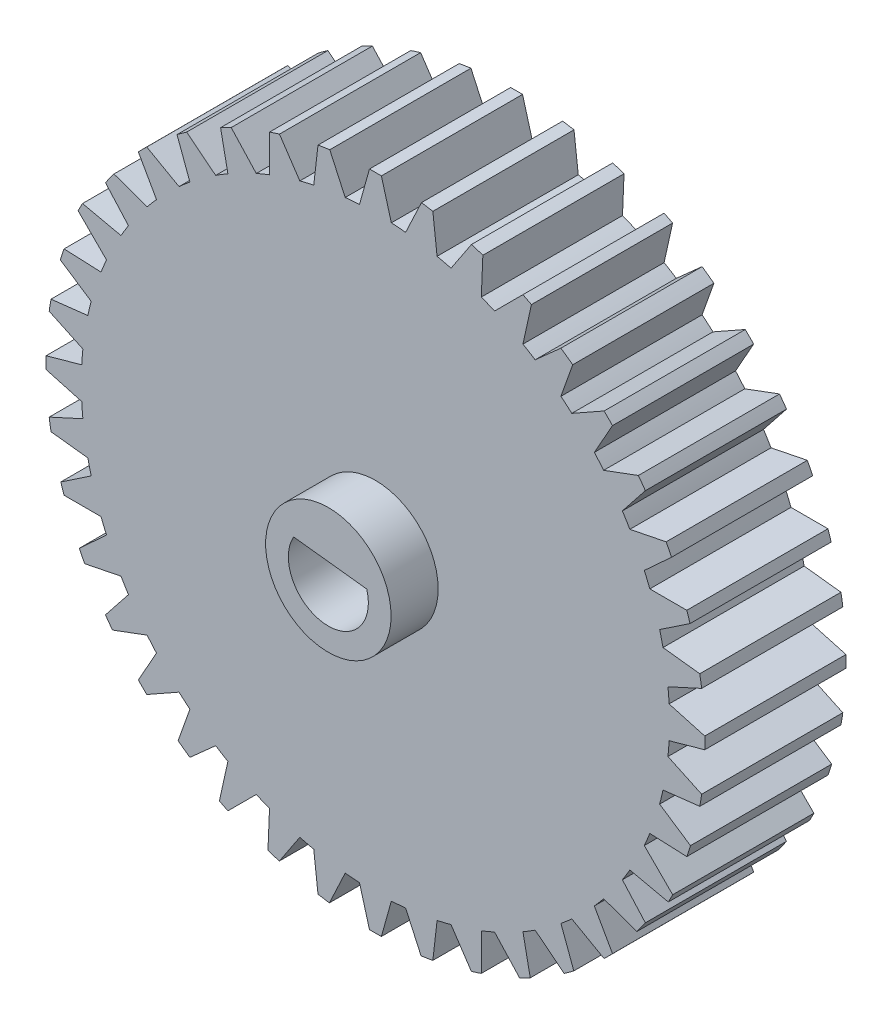
SolidWorks part; units mm, degrees
ref_plane "前视基准面" through (0, 0, 0) normal (0, 0, 1) x (1, 0, 0)
ref_plane "上视基准面" through (0, 0, 0) normal (0, 1, 0) x (1, 0, 0)
ref_plane "右视基准面" through (0, 0, 0) normal (1, 0, 0) x (0, 0, -1)
other "Configuration Table"
sketch "草图1" plane through (0, 0, 0) normal (0, 0, 1) x (1, 0, 0)
  line L0 (4.894, 1.4347) -> (-4.4239, 2.5376)
  circle A0 centre (0, 0) radius 8
  arc A1 (-4.4239, 2.5376) -> (4.894, 1.4347) centre (0, 0) ccw
extrude "凸台-拉伸1" add sketch "草图1" along normal blind 24
sketch "草图2" plane through (0, 0, 0) normal (0, 0, 1) x (1, 0, 0)
  circle A0 centre (0, 0) radius 37.5
  circle A1 centre (0, 0) radius 8
extrude "凸台-拉伸2" add sketch "草图2" along normal blind 18
sketch "草图3" plane through (0, 0, 0) normal (0, 0, 1) x (1, 0, 0)
  line L0 (37.445, 2.0305) -> (41.9931, 0.7606)
  line L1 (41.9931, -0.7606) -> (37.445, -2.0305)
  arc A0 (37.445, -2.0305) -> (37.445, 2.0305) centre (0, 0) ccw
  arc A1 (41.9931, 0.7606) -> (41.9931, -0.7606) centre (0, 0) cw
extrude "凸台-拉伸3" add sketch "草图3" along normal blind 18
sketch "草图4" plane through (0, 0, 0) normal (0, 0, 1) x (1, 0, 0)
  line L0 (36.6663, 7.8632) -> (41.3571, 7.3204)
  line L1 (41.5951, 5.8179) -> (37.3016, 3.8521)
  arc A0 (37.3016, 3.8521) -> (36.6663, 7.8632) centre (0, 0) ccw
  arc A1 (41.3571, 7.3204) -> (41.5951, 5.8179) centre (0, 0) cw
extrude "凸台-拉伸4" add sketch "草图4" along normal blind 18
sketch "草图5" plane through (0, 0, 0) normal (0, 0, 1) x (1, 0, 0)
  line L0 (34.9848, 13.5023) -> (39.7028, 13.5023)
  line L1 (40.1116, 12.2345) -> (36.2398, 9.64)
  arc A0 (36.2398, 9.64) -> (34.9848, 13.5023) centre (0, 0) ccw
  arc A1 (39.7028, 13.5023) -> (40.1116, 12.2345) centre (0, 0) cw
extrude "凸台-拉伸5" add sketch "草图5" along normal blind 18
sketch "草图6" plane through (0, 0, 0) normal (0, 0, 1) x (1, 0, 0)
  line L0 (32.4419, 18.8089) -> (37.0708, 19.7422)
  line L1 (37.7615, 18.3868) -> (34.2856, 15.1904)
  arc A0 (34.2856, 15.1904) -> (32.4419, 18.8089) centre (0, 0) ccw
  arc A1 (37.0708, 19.7422) -> (37.7615, 18.3868) centre (0, 0) cw
extrude "凸台-拉伸6" add sketch "草图6" along normal blind 18
sketch "草图7" plane through (0, 0, 0) normal (0, 0, 1) x (1, 0, 0)
  line L0 (29.1001, 23.6524) -> (33.5261, 25.2983)
  line L1 (34.4202, 24.0676) -> (31.4872, 20.3669)
  arc A0 (31.4872, 20.3669) -> (29.1001, 23.6524) centre (0, 0) ccw
  arc A1 (33.5261, 25.2983) -> (34.4202, 24.0676) centre (0, 0) cw
extrude "凸台-拉伸7" add sketch "草图7" along normal blind 18
sketch "草图8" plane through (0, 0, 0) normal (0, 0, 1) x (1, 0, 0)
  line L0 (25.0418, 27.9134) -> (29.1558, 30.2315)
  line L1 (30.2315, 29.1558) -> (27.9134, 25.0418)
  arc A0 (27.9134, 25.0418) -> (25.0418, 27.9134) centre (0, 0) ccw
  arc A1 (29.1558, 30.2315) -> (30.2315, 29.1558) centre (0, 0) cw
extrude "凸台-拉伸8" add sketch "草图8" along normal blind 18
sketch "草图9" plane through (0, 0, 0) normal (0, 0, 1) x (1, 0, 0)
  line L0 (20.3669, 31.4872) -> (23.6524, 34.4202)
  line L1 (25.1558, 33.3372) -> (23.6524, 29.1001)
  arc A0 (23.6524, 29.1001) -> (20.3669, 31.4872) centre (0, 0) ccw
  arc A1 (23.6524, 34.4202) -> (25.1558, 33.3372) centre (0, 0) cw
extrude "凸台-拉伸9" add sketch "草图9" along normal blind 18
sketch "草图10" plane through (0, 0, 0) normal (0, 0, 1) x (1, 0, 0)
  line L0 (15.1904, 34.2856) -> (18.8089, 37.904)
  line L1 (19.8899, 37.3481) -> (18.8089, 32.4419)
  arc A0 (18.8089, 32.4419) -> (15.1904, 34.2856) centre (0, 0) ccw
  arc A1 (18.8089, 37.904) -> (19.8899, 37.3481) centre (0, 0) cw
extrude "凸台-拉伸10" add sketch "草图10" along normal blind 18
sketch "草图11" plane through (0, 0, 0) normal (0, 0, 1) x (1, 0, 0)
  line L0 (9.64, 36.2398) -> (12.2532, 40.1729)
  line L1 (13.7, 39.7028) -> (13.5023, 34.9848)
  arc A0 (13.5023, 34.9848) -> (9.64, 36.2398) centre (0, 0) ccw
  arc A1 (12.2532, 40.1729) -> (13.7, 39.7028) centre (0, 0) cw
extrude "凸台-拉伸11" add sketch "草图11" along normal blind 18
sketch "草图12" plane through (0, 0, 0) normal (0, 0, 1) x (1, 0, 0)
  line L0 (3.8521, 37.3016) -> (5.8663, 41.5951)
  line L1 (7.3216, 41.3637) -> (7.8632, 36.6663)
  arc A0 (7.8632, 36.6663) -> (3.8521, 37.3016) centre (0, 0) ccw
  arc A1 (5.8663, 41.5951) -> (7.3216, 41.3637) centre (0, 0) cw
extrude "凸台-拉伸12" add sketch "草图12" along normal blind 18
sketch "草图13" plane through (0, 0, 0) normal (0, 0, 1) x (1, 0, 0)
  line L0 (-2.0305, 37.445) -> (-0.7606, 41.9931)
  line L1 (0.7606, 41.9931) -> (2.0305, 37.445)
  arc A0 (2.0305, 37.445) -> (-2.0305, 37.445) centre (0, 0) ccw
  arc A1 (-0.7606, 41.9931) -> (0.7606, 41.9931) centre (0, 0) cw
extrude "凸台-拉伸13" add sketch "草图13" along normal blind 18
sketch "草图14" plane through (0, 0, 0) normal (0, 0, 1) x (1, 0, 0)
  line L0 (-7.8632, 36.6663) -> (-7.3204, 41.3571)
  line L1 (-5.8179, 41.5951) -> (-3.8521, 37.3016)
  arc A0 (-3.8521, 37.3016) -> (-7.8632, 36.6663) centre (0, 0) ccw
  arc A1 (-7.3204, 41.3571) -> (-5.8179, 41.5951) centre (0, 0) cw
extrude "凸台-拉伸14" add sketch "草图14" along normal blind 18
sketch "草图15" plane through (0, 0, 0) normal (0, 0, 1) x (1, 0, 0)
  line L0 (-13.5023, 34.9848) -> (-13.5023, 39.7028)
  line L1 (-12.2345, 40.1116) -> (-9.64, 36.2398)
  arc A0 (-9.64, 36.2398) -> (-13.5023, 34.9848) centre (0, 0) ccw
  arc A1 (-13.5023, 39.7028) -> (-12.2345, 40.1116) centre (0, 0) cw
extrude "凸台-拉伸15" add sketch "草图15" along normal blind 18
sketch "草图16" plane through (0, 0, 0) normal (0, 0, 1) x (1, 0, 0)
  line L0 (-18.8089, 32.4419) -> (-19.7422, 37.0708)
  line L1 (-18.3868, 37.7615) -> (-15.1904, 34.2856)
  arc A0 (-15.1904, 34.2856) -> (-18.8089, 32.4419) centre (0, 0) ccw
  arc A1 (-19.7422, 37.0708) -> (-18.3868, 37.7615) centre (0, 0) cw
extrude "凸台-拉伸16" add sketch "草图16" along normal blind 18
sketch "草图17" plane through (0, 0, 0) normal (0, 0, 1) x (1, 0, 0)
  line L0 (-23.6524, 29.1001) -> (-25.2983, 33.5261)
  line L1 (-24.0676, 34.4202) -> (-20.3669, 31.4872)
  arc A0 (-20.3669, 31.4872) -> (-23.6524, 29.1001) centre (0, 0) ccw
  arc A1 (-25.2983, 33.5261) -> (-24.0676, 34.4202) centre (0, 0) cw
extrude "凸台-拉伸17" add sketch "草图17" along normal blind 18
sketch "草图18" plane through (0, 0, 0) normal (0, 0, 1) x (1, 0, 0)
  line L0 (-27.9134, 25.0418) -> (-30.2315, 29.1558)
  line L1 (-29.1558, 30.2315) -> (-25.0418, 27.9134)
  arc A0 (-25.0418, 27.9134) -> (-27.9134, 25.0418) centre (0, 0) ccw
  arc A1 (-30.2315, 29.1558) -> (-29.1558, 30.2315) centre (0, 0) cw
extrude "凸台-拉伸18" add sketch "草图18" along normal blind 18
sketch "草图19" plane through (0, 0, 0) normal (0, 0, 1) x (1, 0, 0)
  line L0 (-31.4872, 20.3669) -> (-34.4202, 23.6524)
  line L1 (-33.3372, 25.1558) -> (-29.1001, 23.6524)
  arc A0 (-29.1001, 23.6524) -> (-31.4872, 20.3669) centre (0, 0) ccw
  arc A1 (-34.4202, 23.6524) -> (-33.3372, 25.1558) centre (0, 0) cw
extrude "凸台-拉伸19" add sketch "草图19" along normal blind 18
sketch "草图20" plane through (0, 0, 0) normal (0, 0, 1) x (1, 0, 0)
  line L0 (-34.2856, 15.1904) -> (-37.904, 18.8089)
  line L1 (-37.3481, 19.8899) -> (-32.4419, 18.8089)
  arc A0 (-32.4419, 18.8089) -> (-34.2856, 15.1904) centre (0, 0) ccw
  arc A1 (-37.904, 18.8089) -> (-37.3481, 19.8899) centre (0, 0) cw
extrude "凸台-拉伸20" add sketch "草图20" along normal blind 18
sketch "草图21" plane through (0, 0, 0) normal (0, 0, 1) x (1, 0, 0)
  line L0 (-36.2398, 9.64) -> (-40.1729, 12.2532)
  line L1 (-39.7028, 13.7) -> (-34.9848, 13.5023)
  arc A0 (-34.9848, 13.5023) -> (-36.2398, 9.64) centre (0, 0) ccw
  arc A1 (-40.1729, 12.2532) -> (-39.7028, 13.7) centre (0, 0) cw
extrude "凸台-拉伸21" add sketch "草图21" along normal blind 18
sketch "草图22" plane through (0, 0, 0) normal (0, 0, 1) x (1, 0, 0)
  line L0 (-37.3016, 3.8521) -> (-41.5951, 5.8663)
  line L1 (-41.3637, 7.3216) -> (-36.6663, 7.8632)
  arc A0 (-36.6663, 7.8632) -> (-37.3016, 3.8521) centre (0, 0) ccw
  arc A1 (-41.5951, 5.8663) -> (-41.3637, 7.3216) centre (0, 0) cw
extrude "凸台-拉伸22" add sketch "草图22" along normal blind 18
sketch "草图23" plane through (0, 0, 0) normal (0, 0, 1) x (1, 0, 0)
  line L0 (-37.445, -2.0305) -> (-41.9931, -0.7606)
  line L1 (-41.9931, 0.7606) -> (-37.445, 2.0305)
  arc A0 (-37.445, 2.0305) -> (-37.445, -2.0305) centre (0, 0) ccw
  arc A1 (-41.9931, -0.7606) -> (-41.9931, 0.7606) centre (0, 0) cw
extrude "凸台-拉伸23" add sketch "草图23" along normal blind 18
sketch "草图24" plane through (0, 0, 0) normal (0, 0, 1) x (1, 0, 0)
  line L0 (-36.6663, -7.8632) -> (-41.3571, -7.3204)
  line L1 (-41.5951, -5.8179) -> (-37.3016, -3.8521)
  arc A0 (-37.3016, -3.8521) -> (-36.6663, -7.8632) centre (0, 0) ccw
  arc A1 (-41.3571, -7.3204) -> (-41.5951, -5.8179) centre (0, 0) cw
extrude "凸台-拉伸24" add sketch "草图24" along normal blind 18
sketch "草图25" plane through (0, 0, 0) normal (0, 0, 1) x (1, 0, 0)
  line L0 (-34.9848, -13.5023) -> (-39.7028, -13.5023)
  line L1 (-40.1116, -12.2345) -> (-36.2398, -9.64)
  arc A0 (-36.2398, -9.64) -> (-34.9848, -13.5023) centre (0, 0) ccw
  arc A1 (-39.7028, -13.5023) -> (-40.1116, -12.2345) centre (0, 0) cw
extrude "凸台-拉伸25" add sketch "草图25" along normal blind 18
sketch "草图26" plane through (0, 0, 0) normal (0, 0, 1) x (1, 0, 0)
  line L0 (-32.4419, -18.8089) -> (-37.0708, -19.7422)
  line L1 (-37.7615, -18.3868) -> (-34.2856, -15.1904)
  arc A0 (-34.2856, -15.1904) -> (-32.4419, -18.8089) centre (0, 0) ccw
  arc A1 (-37.0708, -19.7422) -> (-37.7615, -18.3868) centre (0, 0) cw
extrude "凸台-拉伸26" add sketch "草图26" along normal blind 18
sketch "草图27" plane through (0, 0, 0) normal (0, 0, 1) x (1, 0, 0)
  line L0 (-29.1001, -23.6524) -> (-33.5261, -25.2983)
  line L1 (-34.4202, -24.0676) -> (-31.4872, -20.3669)
  arc A0 (-31.4872, -20.3669) -> (-29.1001, -23.6524) centre (0, 0) ccw
  arc A1 (-33.5261, -25.2983) -> (-34.4202, -24.0676) centre (0, 0) cw
extrude "凸台-拉伸27" add sketch "草图27" along normal blind 18
sketch "草图28" plane through (0, 0, 0) normal (0, 0, 1) x (1, 0, 0)
  line L0 (-25.0418, -27.9134) -> (-29.1558, -30.2315)
  line L1 (-30.2315, -29.1558) -> (-27.9134, -25.0418)
  arc A0 (-27.9134, -25.0418) -> (-25.0418, -27.9134) centre (0, 0) ccw
  arc A1 (-29.1558, -30.2315) -> (-30.2315, -29.1558) centre (0, 0) cw
extrude "凸台-拉伸28" add sketch "草图28" along normal blind 18
sketch "草图29" plane through (0, 0, 0) normal (0, 0, 1) x (1, 0, 0)
  line L0 (-20.3669, -31.4872) -> (-23.6524, -34.4202)
  line L1 (-25.1558, -33.3372) -> (-23.6524, -29.1001)
  arc A0 (-23.6524, -29.1001) -> (-20.3669, -31.4872) centre (0, 0) ccw
  arc A1 (-23.6524, -34.4202) -> (-25.1558, -33.3372) centre (0, 0) cw
extrude "凸台-拉伸29" add sketch "草图29" along normal blind 18
sketch "草图30" plane through (0, 0, 0) normal (0, 0, 1) x (1, 0, 0)
  line L0 (-15.1904, -34.2856) -> (-18.8089, -37.904)
  line L1 (-19.8899, -37.3481) -> (-18.8089, -32.4419)
  arc A0 (-18.8089, -32.4419) -> (-15.1904, -34.2856) centre (0, 0) ccw
  arc A1 (-18.8089, -37.904) -> (-19.8899, -37.3481) centre (0, 0) cw
extrude "凸台-拉伸30" add sketch "草图30" along normal blind 18
sketch "草图31" plane through (0, 0, 0) normal (0, 0, 1) x (1, 0, 0)
  line L0 (-9.64, -36.2398) -> (-12.2532, -40.1729)
  line L1 (-13.7, -39.7028) -> (-13.5023, -34.9848)
  arc A0 (-13.5023, -34.9848) -> (-9.64, -36.2398) centre (0, 0) ccw
  arc A1 (-12.2532, -40.1729) -> (-13.7, -39.7028) centre (0, 0) cw
extrude "凸台-拉伸31" add sketch "草图31" along normal blind 18
sketch "草图32" plane through (0, 0, 0) normal (0, 0, 1) x (1, 0, 0)
  line L0 (-3.8521, -37.3016) -> (-5.8663, -41.5951)
  line L1 (-7.3216, -41.3637) -> (-7.8632, -36.6663)
  arc A0 (-7.8632, -36.6663) -> (-3.8521, -37.3016) centre (0, 0) ccw
  arc A1 (-5.8663, -41.5951) -> (-7.3216, -41.3637) centre (0, 0) cw
extrude "凸台-拉伸32" add sketch "草图32" along normal blind 18
sketch "草图33" plane through (0, 0, 0) normal (0, 0, 1) x (1, 0, 0)
  line L0 (2.0305, -37.445) -> (0.7606, -41.9931)
  line L1 (-0.7606, -41.9931) -> (-2.0305, -37.445)
  arc A0 (-2.0305, -37.445) -> (2.0305, -37.445) centre (0, 0) ccw
  arc A1 (0.7606, -41.9931) -> (-0.7606, -41.9931) centre (0, 0) cw
extrude "凸台-拉伸33" add sketch "草图33" along normal blind 18
sketch "草图34" plane through (0, 0, 0) normal (0, 0, 1) x (1, 0, 0)
  line L0 (7.8632, -36.6663) -> (7.3204, -41.3571)
  line L1 (5.8179, -41.5951) -> (3.8521, -37.3016)
  arc A0 (3.8521, -37.3016) -> (7.8632, -36.6663) centre (0, 0) ccw
  arc A1 (7.3204, -41.3571) -> (5.8179, -41.5951) centre (0, 0) cw
extrude "凸台-拉伸34" add sketch "草图34" along normal blind 18
sketch "草图35" plane through (0, 0, 0) normal (0, 0, 1) x (1, 0, 0)
  line L0 (13.5023, -34.9848) -> (13.5023, -39.7028)
  line L1 (12.2345, -40.1116) -> (9.64, -36.2398)
  arc A0 (9.64, -36.2398) -> (13.5023, -34.9848) centre (0, 0) ccw
  arc A1 (13.5023, -39.7028) -> (12.2345, -40.1116) centre (0, 0) cw
extrude "凸台-拉伸35" add sketch "草图35" along normal blind 18
sketch "草图36" plane through (0, 0, 0) normal (0, 0, 1) x (1, 0, 0)
  line L0 (18.8089, -32.4419) -> (19.7422, -37.0708)
  line L1 (18.3868, -37.7615) -> (15.1904, -34.2856)
  arc A0 (15.1904, -34.2856) -> (18.8089, -32.4419) centre (0, 0) ccw
  arc A1 (19.7422, -37.0708) -> (18.3868, -37.7615) centre (0, 0) cw
extrude "凸台-拉伸36" add sketch "草图36" along normal blind 18
sketch "草图37" plane through (0, 0, 0) normal (0, 0, 1) x (1, 0, 0)
  line L0 (23.6524, -29.1001) -> (25.2983, -33.5261)
  line L1 (24.0676, -34.4202) -> (20.3669, -31.4872)
  arc A0 (20.3669, -31.4872) -> (23.6524, -29.1001) centre (0, 0) ccw
  arc A1 (25.2983, -33.5261) -> (24.0676, -34.4202) centre (0, 0) cw
extrude "凸台-拉伸37" add sketch "草图37" along normal blind 18
sketch "草图38" plane through (0, 0, 0) normal (0, 0, 1) x (1, 0, 0)
  line L0 (27.9134, -25.0418) -> (30.2315, -29.1558)
  line L1 (29.1558, -30.2315) -> (25.0418, -27.9134)
  arc A0 (25.0418, -27.9134) -> (27.9134, -25.0418) centre (0, 0) ccw
  arc A1 (30.2315, -29.1558) -> (29.1558, -30.2315) centre (0, 0) cw
extrude "凸台-拉伸38" add sketch "草图38" along normal blind 18
sketch "草图39" plane through (0, 0, 0) normal (0, 0, 1) x (1, 0, 0)
  line L0 (31.4872, -20.3669) -> (34.4202, -23.6524)
  line L1 (33.3372, -25.1558) -> (29.1001, -23.6524)
  arc A0 (29.1001, -23.6524) -> (31.4872, -20.3669) centre (0, 0) ccw
  arc A1 (34.4202, -23.6524) -> (33.3372, -25.1558) centre (0, 0) cw
extrude "凸台-拉伸39" add sketch "草图39" along normal blind 18
sketch "草图40" plane through (0, 0, 0) normal (0, 0, 1) x (1, 0, 0)
  line L0 (34.2856, -15.1904) -> (37.904, -18.8089)
  line L1 (37.3481, -19.8899) -> (32.4419, -18.8089)
  arc A0 (32.4419, -18.8089) -> (34.2856, -15.1904) centre (0, 0) ccw
  arc A1 (37.904, -18.8089) -> (37.3481, -19.8899) centre (0, 0) cw
extrude "凸台-拉伸40" add sketch "草图40" along normal blind 18
sketch "草图41" plane through (0, 0, 0) normal (0, 0, 1) x (1, 0, 0)
  line L0 (36.2398, -9.64) -> (40.1729, -12.2532)
  line L1 (39.7028, -13.7) -> (34.9848, -13.5023)
  arc A0 (34.9848, -13.5023) -> (36.2398, -9.64) centre (0, 0) ccw
  arc A1 (40.1729, -12.2532) -> (39.7028, -13.7) centre (0, 0) cw
extrude "凸台-拉伸41" add sketch "草图41" along normal blind 18
sketch "草图42" plane through (0, 0, 0) normal (0, 0, 1) x (1, 0, 0)
  line L0 (37.3016, -3.8521) -> (41.5951, -5.8663)
  line L1 (41.3637, -7.3216) -> (36.6663, -7.8632)
  arc A0 (36.6663, -7.8632) -> (37.3016, -3.8521) centre (0, 0) ccw
  arc A1 (41.5951, -5.8663) -> (41.3637, -7.3216) centre (0, 0) cw
extrude "凸台-拉伸42" add sketch "草图42" along normal blind 18
